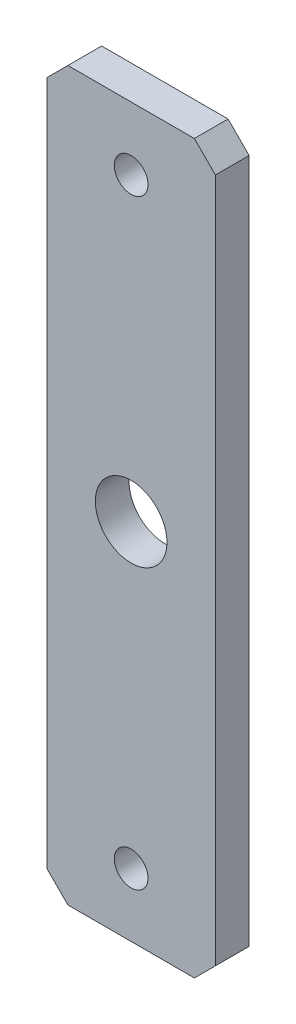
SolidWorks part; units mm, degrees
ref_plane "前视基准面" through (0, 0, 0) normal (0, 0, 1) x (1, 0, 0)
ref_plane "上视基准面" through (0, 0, 0) normal (0, 1, 0) x (1, 0, 0)
ref_plane "右视基准面" through (0, 0, 0) normal (1, 0, 0) x (0, 0, -1)
sketch "草图1" plane through (0, 0, 0) normal (0, 0, 1) x (1, 0, 0)
  line L1 (0, 0) -> (80, 0)
  line L2 (0, 0) -> (0, 345)
  line L3 (0, 345) -> (80, 345)
  line L4 (80, 0) -> (80, 345)
  dimension "D1" = 80
  dimension "D2" = 345
extrude "凸台-拉伸1" add sketch "草图1" along normal blind 16
hole_wizard "Ø16.0 (16) 直径孔1" positions "草图2" profile "草图3" hole size "Ø16.0" standard "GB"
sketch "草图2" plane through (0, 0, 16) normal (0, 0, 1) x (1, 0, 0)
  line L0 (80, 0) -> (80, 345) construction
  line L1 (0, 172.5) -> (80, 172.5) construction
  line L2 (0, 345) -> (0, 0) construction
  point P0 (40, 315)
  point P2 (40, 30)
  dimension "D1" = 285
  dimension "D2" = 40
sketch "草图3" plane through (40, 315, 16) normal (1, 0, 0) x (0, -1, 0)
  line L0 (0, 0) -> (0, 42.8069)
  line L1 (0, 42.8069) -> (8, 38)
  line L2 (8, 38) -> (8, 0)
  line L5 (8, 0) -> (0, 0)
  line L10 (0, 42.8069) -> (-8, 38) construction
  line L11 (0, -6.35) -> (0, 107.95) construction
  dimension "孔直径" = 16
  dimension "孔深度" = 38
  dimension "导头角度" = 118
chamfer "倒角1" distance 10 angle 45 4 edges at (0, 0, 8) (80, 0, 8) (80, 345, 8) (0, 345, 8)
hole_wizard "Ø16.0 (16) 直径孔2" positions "草图4" profile "草图5" hole size "Ø16.0" standard "GB" end condition through all
sketch "草图4" plane through (0, 0, 16) normal (0, 0, 1) x (1, 0, 0)
  line L2 (0, 172.5) -> (80, 172.5) construction
  line L3 (0, 335) -> (0, 10) construction
  line L4 (80, 10) -> (80, 335) construction
  point P0 (40, 172.5)
  point P14 (38.7867, 172.5)
  point P15 (35.6512, 172.5)
  point P16 (37.7907, 172.5)
  dimension "D1" = 40
sketch "草图5" plane through (40, 172.5, 16) normal (1, 0, 0) x (0, -1, 0)
  line L0 (0, 0) -> (0, 16)
  line L1 (0, 16) -> (17, 16)
  line L2 (17, 16) -> (17, 0)
  line L5 (17, 0) -> (0, 0)
  line L11 (0, -6.35) -> (0, 107.95) construction
  dimension "通孔孔直径" = 34
  dimension "通孔孔深度" = 16
